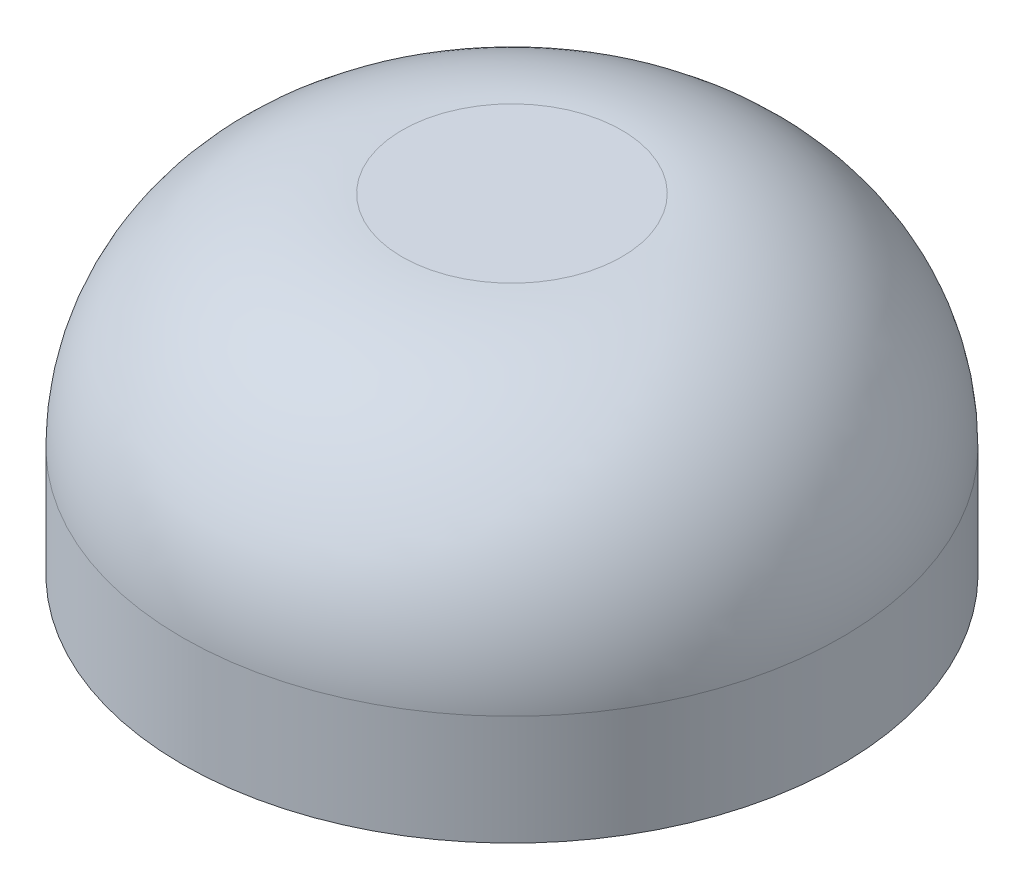
SolidWorks part; units mm, degrees
ref_plane "Plan de face" through (0, 0, 0) normal (0, 0, 1) x (1, 0, 0)
ref_plane "Plan de dessus" through (0, 0, 0) normal (0, 1, 0) x (1, 0, 0)
ref_plane "Plan de droite" through (0, 0, 0) normal (1, 0, 0) x (0, 0, -1)
sketch "Esquisse1" plane through (0, 0, 0) normal (0, 1, 0) x (1, 0, 0)
  circle A0 centre (0, 0) radius 15
extrude "Boss.-Extru.1" add sketch "Esquisse1" along normal blind 15
fillet "Congé1" radius 10 1 edges at (0, 15, 15)
